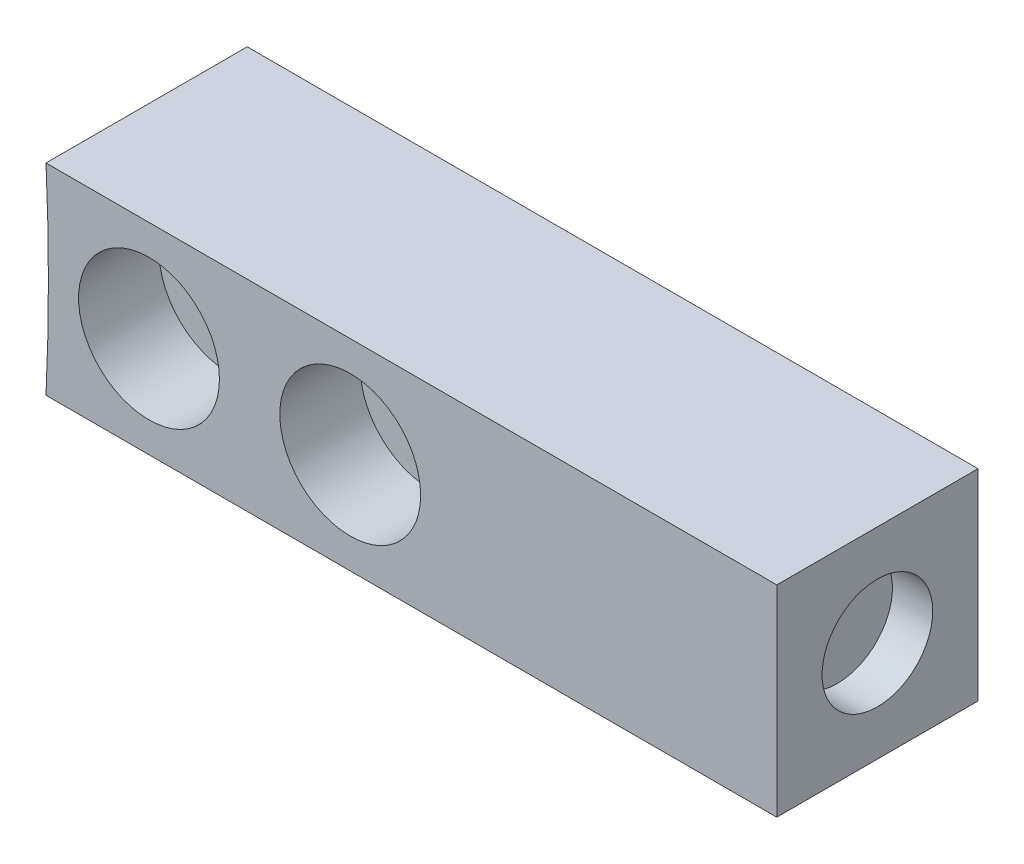
SolidWorks part; units mm, degrees
ref_plane "Plan de face" through (0, 0, 0) normal (0, 0, 1) x (1, 0, 0)
ref_plane "Plan de dessus" through (0, 0, 0) normal (0, 1, 0) x (1, 0, 0)
ref_plane "Plan de droite" through (0, 0, 0) normal (1, 0, 0) x (0, 0, -1)
sketch "Esquisse1" plane through (0, 0, 0) normal (0, 0, 1) x (1, 0, 0)
  line L0 (105, 0) -> (115, 0) construction
  line L1 (104.8809, 5) -> (141.2, 5)
  line L3 (104.8809, -5) -> (141.2, -5)
  line L4 (141.2, 5) -> (141.2, -5)
  line L5 (115, 0) -> (125, 0) construction
  line L6 (125, 0) -> (141.2, 0) construction
  circle A0 centre (110, 0) radius 1.75
  circle A1 centre (120, 0) radius 1.75
  arc A2 (104.8809, 5) -> (104.8809, -5) centre (0, 0) cw
  point P2 (0, 0)
  point P10 (0, 0)
  point P13 (110, 0)
  point P15 (120, 0)
  point P17 (0, 0)
  point P18 (0, 0)
  point P19 (105, 0)
  dimension "D1" = 3.5
  dimension "D4" = 105
  dimension "D2" = 10
  dimension "D3" = 20
  dimension "D5" = 141.2
extrude "Boss.-Extru.1" add sketch "Esquisse1" along normal blind 10
sketch "Esquisse2" plane through (141.2, 0, 0) normal (1, 0, 0) x (0, 0, -1)
  line L0 (-10, 5) -> (0, -5) construction
  circle A0 centre (-5, 0) radius 2.75
  dimension "D1" = 5.5
extrude "Enlèv. mat.-Extru.1" cut sketch "Esquisse2" against normal blind 2
sketch "Esquisse3" plane through (0, 0, 10) normal (0, 0, 1) x (1, 0, 0)
  circle A0 centre (110, 0) radius 3.5
  circle A1 centre (120, 0) radius 3.5
  dimension "D1" = 7
extrude "Enlèv. mat.-Extru.2" cut sketch "Esquisse3" against normal blind 4
